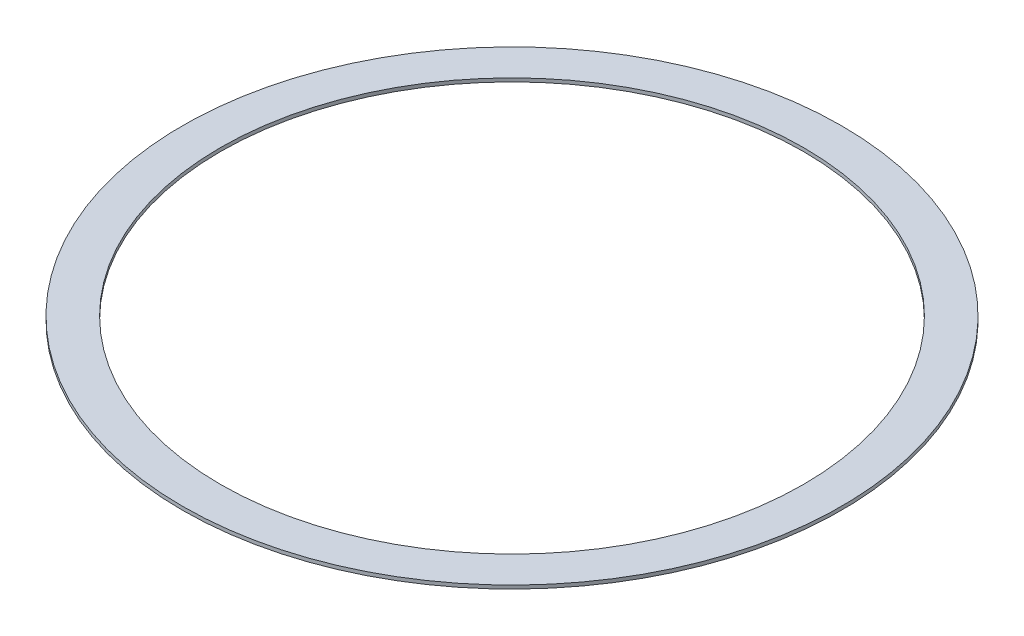
SolidWorks part; units mm, degrees
ref_plane "Front Plane" through (0, 0, 0) normal (0, 0, 1) x (1, 0, 0)
ref_plane "Top Plane" through (0, 0, 0) normal (0, 1, 0) x (1, 0, 0)
ref_plane "Right Plane" through (0, 0, 0) normal (1, 0, 0) x (0, 0, -1)
sketch "Sketch1" plane through (0, 0, 0) normal (0, 1, 0) x (1, 0, 0)
  circle A0 centre (0, 0) radius 71.755
  circle A1 centre (0, 0) radius 63.5
extrude "Boss-Extrude2" add sketch "Sketch1" along normal blind 0.762 contours A0 | A1
